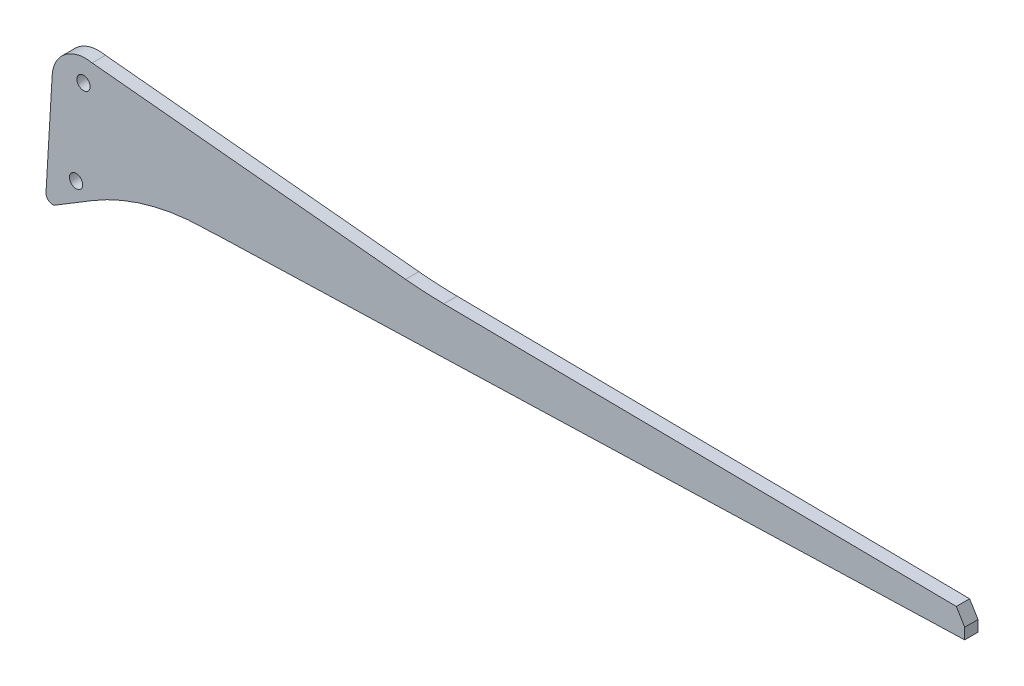
SolidWorks part; units mm, degrees
material "Cast Alloy Steel"
ref_plane "Front Plane" through (0, 0, 0) normal (0, 0, 1) x (1, 0, 0)
ref_plane "Top Plane" through (0, 0, 0) normal (0, 1, 0) x (1, 0, 0)
ref_plane "Right Plane" through (0, 0, 0) normal (1, 0, 0) x (0, 0, -1)
sketch "Sketch1" plane through (0, 0, 0) normal (0, 0, 1) x (1, 0, 0)
  line L10 (236.3465, 61.328) -> (233.5572, 14.0585)
  line L15 (237.2663, 10.968) -> (254.3775, 21.3401)
  line L19 (277.1696, 38.7104) -> (277.1696, 35.81)
  line L21 (254.3775, 75.1296) -> (395.7879, 61.2853)
  line L22 (413.0076, 60.3466) -> (644.2321, 57.725)
  line L23 (644.2321, 57.725) -> (648.0064, 51.4983)
  line L24 (648.0064, 46.528) -> (648.0064, 51.4983)
  line L25 (311.7667, 36.1127) -> (648.0064, 46.528)
  circle A3 centre (250.4809, 65.3734) radius 3
  circle A4 centre (247.1235, 25.3734) radius 3
  arc A5 (254.3775, 75.1296) -> (236.3465, 61.328) centre (251.3204, 60.4444) ccw
  arc A6 (233.5572, 14.0585) -> (237.2663, 10.968) centre (236.5519, 13.8817) ccw
  arc A11 (305.1132, 35.8177) -> (254.3775, 21.3401) centre (306.2135, -64.1762) ccw
  arc A14 (305.1132, 35.8177) -> (311.7667, 36.1127) centre (304.013, 135.8117) ccw
  arc A15 (413.0076, 60.3466) -> (395.7879, 61.2853) centre (415.275, 260.3337) cw
  point P22 (404.3775, 60.4444)
  dimension "D5" = 15
  dimension "D6" = 3
  dimension "D7" = 200
  dimension "D9" = 6
  dimension "D10" = 6
  dimension "D2" = 100
  dimension "D3" = 100
  dimension "D4" = 150
  dimension "D8" = 40
  dimension "D11" = 13.8715
  dimension "D12" = 5
extrude "Boss-Extrude3" add sketch "Sketch1" against normal blind 6
scale "Scale1" scale about centroid uniform scaling yes scale factor 0.5
